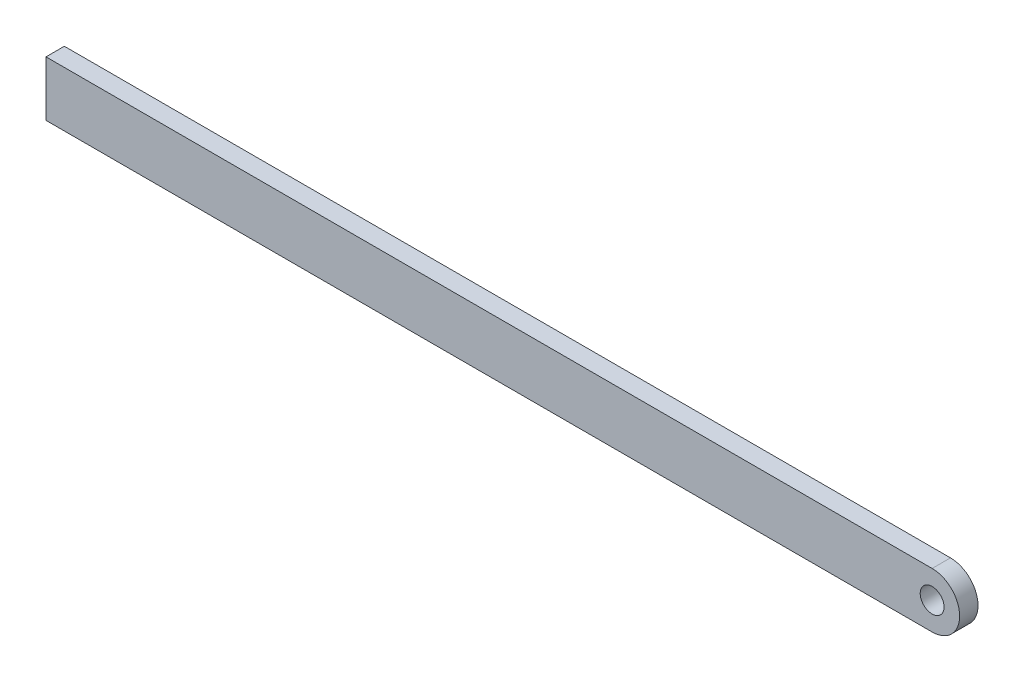
SolidWorks part; units mm, degrees
ref_plane "Front Plane" through (0, 0, 0) normal (0, 0, 1) x (1, 0, 0)
ref_plane "Top Plane" through (0, 0, 0) normal (0, 1, 0) x (1, 0, 0)
ref_plane "Right Plane" through (0, 0, 0) normal (1, 0, 0) x (0, 0, -1)
sketch "Sketch1" plane through (0, 0, 0) normal (0, 0, 1) x (1, 0, 0)
  line L0 (0, 0) -> (241.46, 0) construction
  line L1 (0, 7.5) -> (241.46, 7.5)
  line L2 (0, -7.5) -> (241.46, -7.5)
  line L3 (0, 7.5) -> (0, -7.5)
  circle A0 centre (241.46, 0) radius 3.25
  arc A1 (241.46, -7.5) -> (241.46, 7.5) centre (241.46, 0) ccw
  point P3 (120.73, 0)
  dimension "D3" = 6.5
  dimension "D1" = 241.46
  dimension "D2" = 15
extrude "Boss-Extrude1" add sketch "Sketch1" along normal mid plane 5
